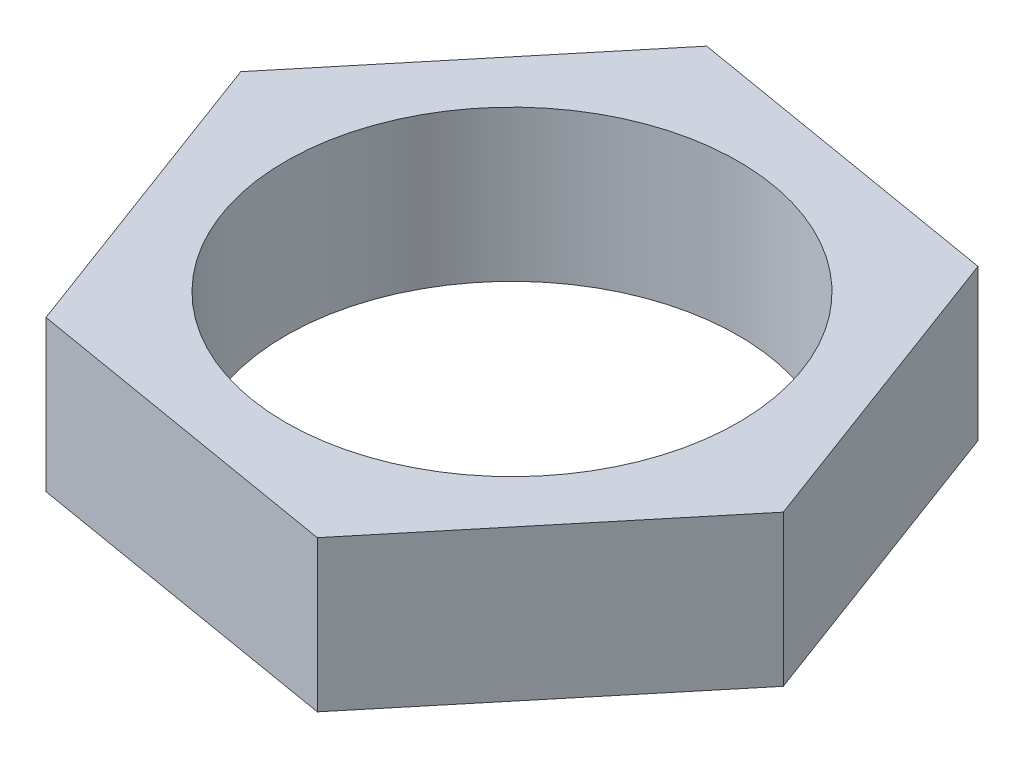
SolidWorks part; units mm, degrees
ref_plane "Front Plane" through (0, 0, 0) normal (0, 0, 1) x (1, 0, 0)
ref_plane "Top Plane" through (0, 0, 0) normal (0, 1, 0) x (1, 0, 0)
ref_plane "Right Plane" through (0, 0, 0) normal (1, 0, 0) x (0, 0, -1)
sketch "Szkic1" plane through (0, 0, 0) normal (0, 1, 0) x (1, 0, 0)
  line L1 (-10.8167, 1.8253) -> (-6.9891, -8.4549)
  line L2 (-6.9891, -8.4549) -> (3.8276, -10.2802)
  line L3 (3.8276, -10.2802) -> (10.8167, -1.8253)
  line L4 (10.8167, -1.8253) -> (6.9891, 8.4549)
  line L5 (6.9891, 8.4549) -> (-3.8276, 10.2802)
  line L6 (-3.8276, 10.2802) -> (-10.8167, 1.8253)
  circle A0 centre (0, 0) radius 9.5 construction
  circle A1 centre (0, 0) radius 7.5
  dimension "D2" = 15
  dimension "D1" = 19
extrude "Dodanie-wyciągnięcie1" add sketch "Szkic1" along normal blind 5
